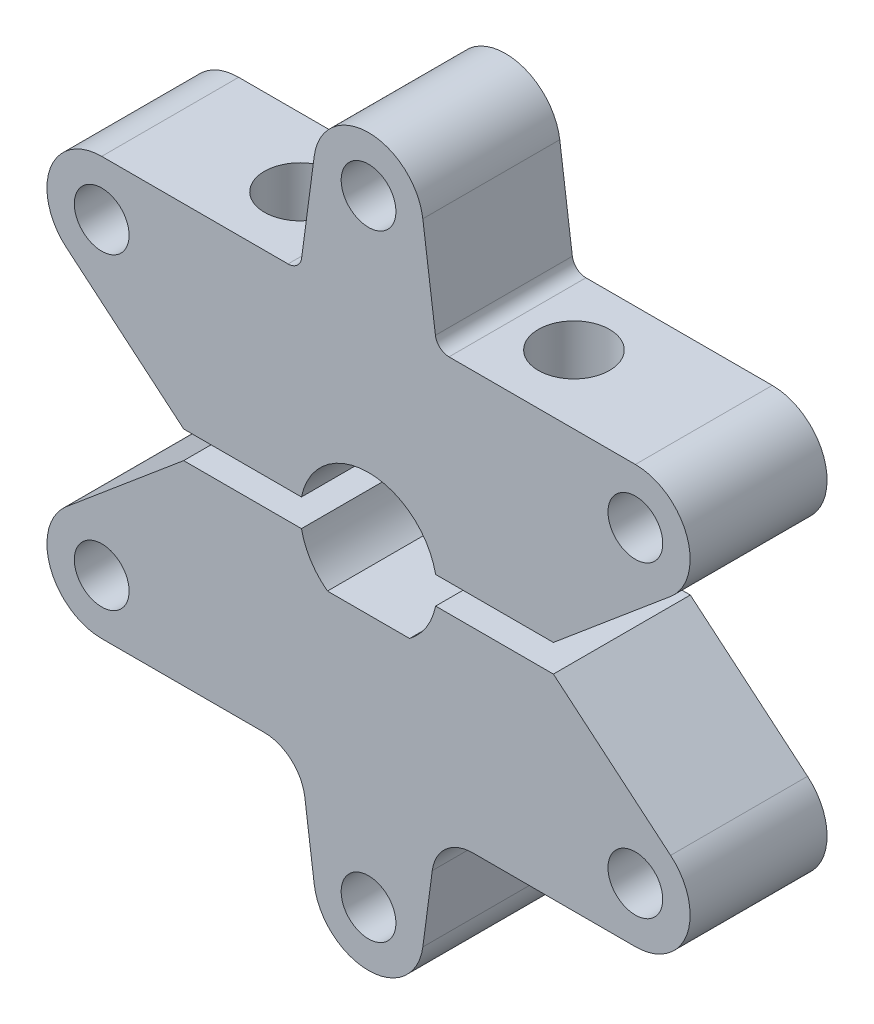
SolidWorks part; units mm, degrees
material "6061 合金"
ref_plane "前视基准面" through (0, 0, 0) normal (0, 0, 1) x (1, 0, 0)
ref_plane "上视基准面" through (0, 0, 0) normal (0, 1, 0) x (1, 0, 0)
ref_plane "右视基准面" through (0, 0, 0) normal (1, 0, 0) x (0, 0, -1)
sketch "草图1" plane through (0, 0, 0) normal (0, 0, 1) x (1, 0, 0)
  line L0 (-3, -4) -> (3, -4)
  line L6 (-19.4856, -15.25) -> (19.4856, -15.25)
  line L7 (-13.5, 1) -> (-4.899, 1)
  line L8 (0, 0) -> (0, -15.25) construction
  line L9 (-22.058, 8.1869) -> (-13.5, 1)
  line L10 (-22.058, -8.1869) -> (-13.5, -1)
  line L11 (-13.5, -1) -> (-4.899, -1)
  line L12 (13.5, -1) -> (22.058, -8.1869)
  line L13 (-22.5, 0) -> (22.5, 0) construction
  line L14 (-19.4856, 15.25) -> (19.4856, 15.25)
  line L15 (13.5, 1) -> (22.058, 8.1869)
  line L16 (4.899, 1) -> (13.5, 1)
  line L17 (4.899, -1) -> (13.5, -1)
  arc A0 (3, -4) -> (4.899, -1) centre (0, 0) ccw
  circle A1 centre (0, 0) radius 22.5 construction
  circle A2 centre (0, 22.5) radius 2 construction
  circle A3 centre (19.4856, 11.25) radius 2
  circle A4 centre (19.4856, -11.25) radius 2
  circle A5 centre (0, -22.5) radius 2 construction
  circle A6 centre (-19.4856, -11.25) radius 2
  circle A7 centre (-19.4856, 11.25) radius 2
  arc A10 (-22.058, -8.1869) -> (-19.4856, -15.25) centre (-19.4856, -11.25) ccw
  arc A12 (19.4856, -15.25) -> (22.058, -8.1869) centre (19.4856, -11.25) ccw
  arc A13 (-22.058, 8.1869) -> (-19.4856, 15.25) centre (-19.4856, 11.25) cw
  arc A14 (19.4856, 15.25) -> (22.058, 8.1869) centre (19.4856, 11.25) cw
  arc A15 (-4.899, -1) -> (-3, -4) centre (0, 0) ccw
  arc A16 (4.899, 1) -> (-4.899, 1) centre (0, 0) ccw
  point P19 (0, 0)
  dimension "D1" = 10
  dimension "D3" = 45
  dimension "D5" = 4
  dimension "D6" = 4
  dimension "D2" = 4
  dimension "D9" = 2
  dimension "D10" = 27
  dimension "D4" = 6
extrude "凸台-拉伸1" add sketch "草图1" along normal blind 10
sketch "草图3" plane through (0, 15.25, 0) normal (0, 1, 0) x (1, 0, 0)
  line L0 (10, -5) -> (-10, -5) construction
  line L1 (0, -10) -> (0, -5) construction
  line L2 (19.4856, -10) -> (-19.4856, -10) construction
  line L3 (0, -5) -> (0, 0) construction
  circle A0 centre (10, -5) radius 2.6
  circle A1 centre (-10, -5) radius 2.6
  dimension "D1" = 5.2
  dimension "D2" = 20
extrude "切除-拉伸2" cut sketch "草图3" against normal up to next (14.25 mm away) and the other way through all
sketch "草图4" plane through (0, 15.25, 0) normal (0, 1, 0) x (1, 0, 0)
  circle A0 centre (10, -5) radius 2
  circle A1 centre (-10, -5) radius 2
  dimension "D1" = 4
extrude "切除-拉伸3" cut sketch "草图4" against normal through all
cosmetic thread "装饰螺纹线5" parameters "D2"=5
cosmetic thread "装饰螺纹线6" parameters "D2"=5
sketch "草图5" plane through (0, 0, 0) normal (0, 0, -1) x (-1, 0, 0)
  line L0 (-3.965, -23.0276) -> (-5, -15.25)
  line L1 (19.4856, -15.25) -> (-19.4856, -15.25) construction
  line L2 (-5, -15.25) -> (5, -15.25)
  line L3 (5, -15.25) -> (3.965, -23.0276)
  line L4 (-22.5, 0) -> (22.5, 0) construction
  line L5 (5, 15.25) -> (3.965, 23.0276)
  line L6 (-5, 15.25) -> (5, 15.25)
  line L7 (-3.965, 23.0276) -> (-5, 15.25)
  circle A1 centre (0, -22.5) radius 2
  circle A3 centre (0, -22.5) radius 2 construction
  arc A5 (-3.965, -23.0276) -> (3.965, -23.0276) centre (0, -22.5) ccw
  arc A7 (19.4856, -15.25) -> (22.058, -8.1869) centre (19.4856, -11.25) ccw construction
  arc A8 (-3.965, 23.0276) -> (3.965, 23.0276) centre (0, 22.5) cw
  circle A9 centre (0, 22.5) radius 2
  dimension "D1" = 10
extrude "凸台-拉伸2" add sketch "草图5" against normal up to surface (10 mm away) up to face at (0, 7.0843, 10)
fillet "圆角1" radius 3 2 edges at (-5, -15.25, 5) (5, -15.25, 5)
fillet "圆角2" radius 1 2 edges at (-5, 15.25, 5) (5, 15.25, 5)
